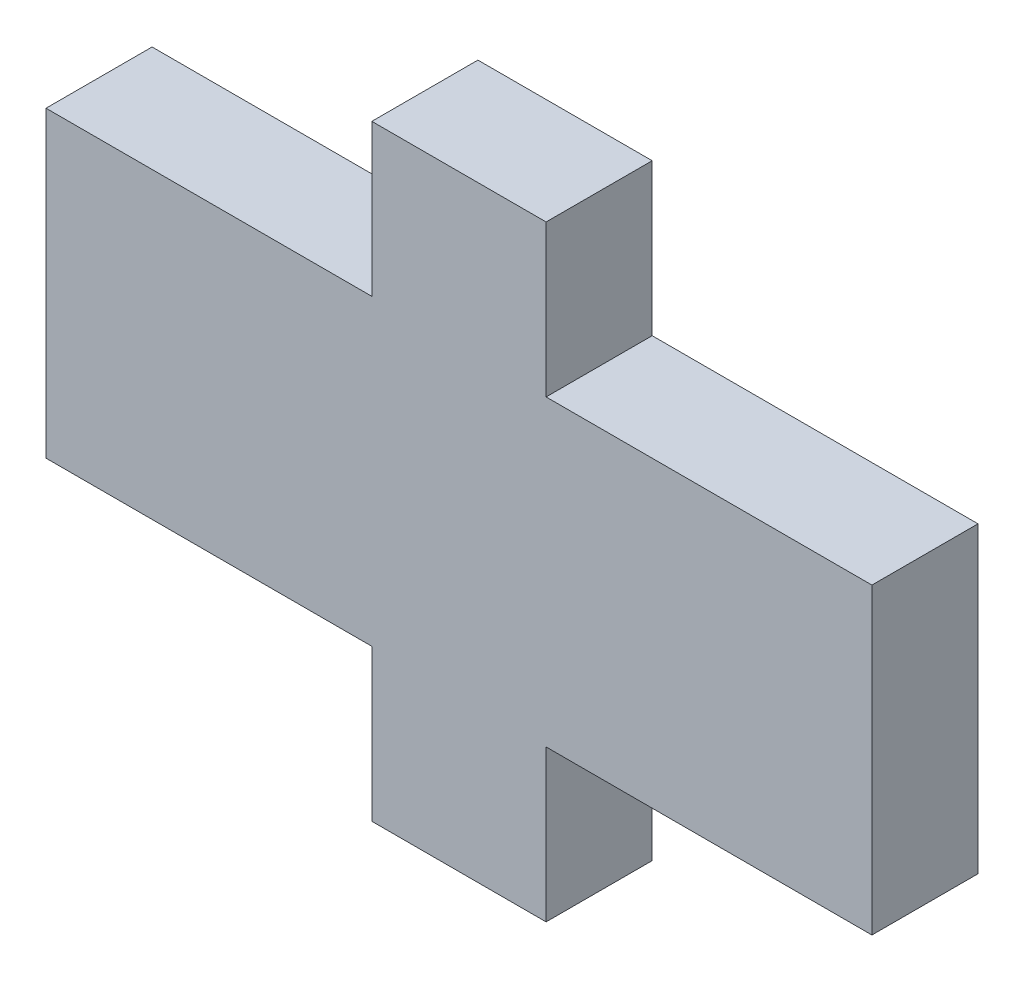
SolidWorks part; units mm, degrees
ref_plane "Front Plane" through (0, 0, 0) normal (0, 0, 1) x (1, 0, 0)
ref_plane "Top Plane" through (0, 0, 0) normal (0, 1, 0) x (1, 0, 0)
ref_plane "Right Plane" through (0, 0, 0) normal (1, 0, 0) x (0, 0, -1)
sketch "Sketch1" plane through (0, 0, 0) normal (0, 0, 1) x (1, 0, 0)
  line L0 (0, 90.1073) -> (0, -126.6779) construction
  line L1 (-49.5455, 0) -> (51.9697, 0) construction
  line L3 (20, 0) -> (-20, 0)
  line L4 (20, 0) -> (20, 73.5)
  line L5 (20, 73.5) -> (-20, 73.5)
  line L6 (-20, 0) -> (-20, 73.5)
  line L7 (20, -78.5) -> (20, -5)
  line L8 (20, -78.5) -> (-20, -78.5)
  line L9 (-20, -78.5) -> (-20, -5)
  line L10 (20, -5) -> (-20, -5)
  line L12 (-63, 34.25) -> (-23, 34.25)
  line L13 (-63, 34.25) -> (-63, -39.25)
  line L14 (-63, -39.25) -> (-23, -39.25)
  line L15 (-23, 34.25) -> (-23, -39.25)
  line L16 (-120.4545, -2.5) -> (121.4673, -2.5) construction
  line L17 (-106, 34.25) -> (-106, -39.25)
  line L18 (-106, 34.25) -> (-66, 34.25)
  line L19 (-66, 34.25) -> (-66, -39.25)
  line L20 (-106, -39.25) -> (-66, -39.25)
  line L21 (63, -39.25) -> (23, -39.25)
  line L22 (23, 34.25) -> (23, -39.25)
  line L23 (63, 34.25) -> (23, 34.25)
  line L24 (63, 34.25) -> (63, -39.25)
  line L25 (106, 34.25) -> (66, 34.25)
  line L26 (66, 34.25) -> (66, -39.25)
  line L27 (106, -39.25) -> (66, -39.25)
  line L28 (106, 34.25) -> (106, -39.25)
  line L29 (-109, -42.5) -> (-109, 37.5)
  line L30 (-109, 37.5) -> (-23, 37.5)
  line L31 (-23, 37.5) -> (-23, 77.5)
  line L32 (-23, 77.5) -> (23, 77.5)
  line L33 (23, 37.5) -> (23, 77.5)
  line L34 (109, 37.5) -> (23, 37.5)
  line L35 (109, -42.5) -> (109, 37.5)
  line L36 (109, -42.5) -> (23, -42.5)
  line L37 (23, -42.5) -> (23, -82.5)
  line L38 (-23, -82.5) -> (23, -82.5)
  line L39 (-23, -42.5) -> (-23, -82.5)
  line L40 (-109, -42.5) -> (-23, -42.5)
  point P37 (0, 77.5)
  point P41 (109, -2.5)
  point P46 (-109, -2.5)
  dimension "D1" = 2
  dimension "D2" = 73.5
  dimension "D3" = 40
  dimension "D4" = 20
  dimension "D6" = 40
  dimension "D5" = 5
  dimension "D7" = 73.5
  dimension "D8" = 2.5
  dimension "D9" = 36.75
  dimension "D10" = 3
  dimension "D12" = 3
  dimension "D13" = 109
  dimension "D14" = 40
  dimension "D15" = 23
  dimension "D16" = 80
  dimension "D11" = 2
sketch "Sketch2" plane through (0, 0, 0) normal (0, 0, 1) x (1, 0, 0)
  line L0 (-109, -42.5) -> (-23, -42.5) construction
  line L1 (-23, -42.5) -> (-23, -82.5) construction
  line L2 (-23, -82.5) -> (23, -82.5) construction
  line L3 (23, -42.5) -> (23, -82.5) construction
  line L4 (109, -42.5) -> (23, -42.5) construction
  line L5 (109, -42.5) -> (109, 37.5) construction
  line L6 (109, 37.5) -> (23, 37.5) construction
  line L7 (23, 37.5) -> (23, 77.5) construction
  line L8 (-23, 77.5) -> (23, 77.5) construction
  line L9 (-23, 37.5) -> (-23, 77.5) construction
  line L10 (-109, 37.5) -> (-23, 37.5) construction
  line L11 (-109, -42.5) -> (-109, 37.5) construction
  line L12 (-109, -42.5) -> (-23, -42.5)
  line L13 (-23, -42.5) -> (-23, -82.5)
  line L14 (-23, -82.5) -> (23, -82.5)
  line L15 (23, -42.5) -> (23, -82.5)
  line L16 (109, -42.5) -> (23, -42.5)
  line L17 (109, -42.5) -> (109, 37.5)
  line L18 (109, 37.5) -> (23, 37.5)
  line L19 (23, 37.5) -> (23, 77.5)
  line L20 (-23, 77.5) -> (23, 77.5)
  line L21 (-23, 37.5) -> (-23, 77.5)
  line L22 (-109, 37.5) -> (-23, 37.5)
  line L23 (-109, -42.5) -> (-109, 37.5)
extrude "Boss-Extrude1" add sketch "Sketch2" along normal blind 28
